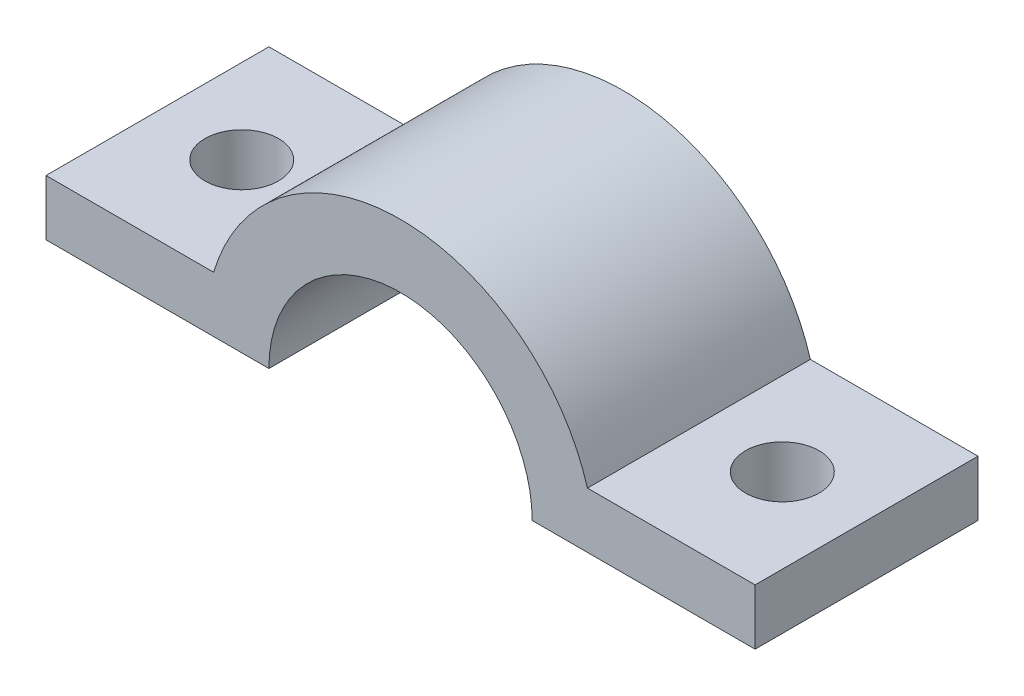
SolidWorks part; units mm, degrees
ref_plane "Front Plane" through (0, 0, 0) normal (0, 0, 1) x (1, 0, 0)
ref_plane "Top Plane" through (0, 0, 0) normal (0, 1, 0) x (1, 0, 0)
ref_plane "Right Plane" through (0, 0, 0) normal (1, 0, 0) x (0, 0, -1)
sketch "Sketch1" plane through (0, 0, 0) normal (0, 0, 1) x (1, 0, 0)
  line L2 (-40.4, 0) -> (-15, 0)
  line L5 (-21.2985, 6.35) -> (-40.4, 6.35)
  line L6 (-40.4, 0) -> (-40.4, 6.35)
  line L10 (0, 0) -> (0, 10.9887) construction
  line L12 (40.4, 0) -> (40.4, 6.35)
  line L13 (21.2985, 6.35) -> (40.4, 6.35)
  line L14 (15, 0) -> (40.4, 0)
  arc A0 (15, 0) -> (-15, 0) centre (0, 0) ccw
  arc A1 (21.2985, 6.35) -> (-21.2985, 6.35) centre (0, 0) ccw
  dimension "D1" = 30
  dimension "D2" = 44.45
  dimension "D3" = 25.4
  dimension "D4" = 6.35
extrude "Boss-Extrude1" add sketch "Sketch1" along normal blind 25.4
sketch "Sketch2" plane through (0, 6.35, 0) normal (0, 1, 0) x (1, 0, 0)
  line L0 (-21.2985, -25.4) -> (-40.4, -25.4) construction
  line L1 (-21.2985, -25.4) -> (-21.2985, 0) construction
  line L2 (21.2985, -25.4) -> (21.2985, 0) construction
  line L3 (40.4, -25.4) -> (21.2985, -25.4) construction
  circle A0 centre (-30.7985, -12.7) radius 4.191
  circle A1 centre (30.7986, -12.7) radius 4.191
  dimension "D1" = 8.382
  dimension "D2" = 12.7
  dimension "D3" = 9.5
  dimension "D4" = 8.382
  dimension "D5" = 9.5
  dimension "D6" = 12.7
extrude "Cut-Extrude1" cut sketch "Sketch2" against normal up to surface (6.35 mm away) up to face at (-27.7, 0, 12.7)
